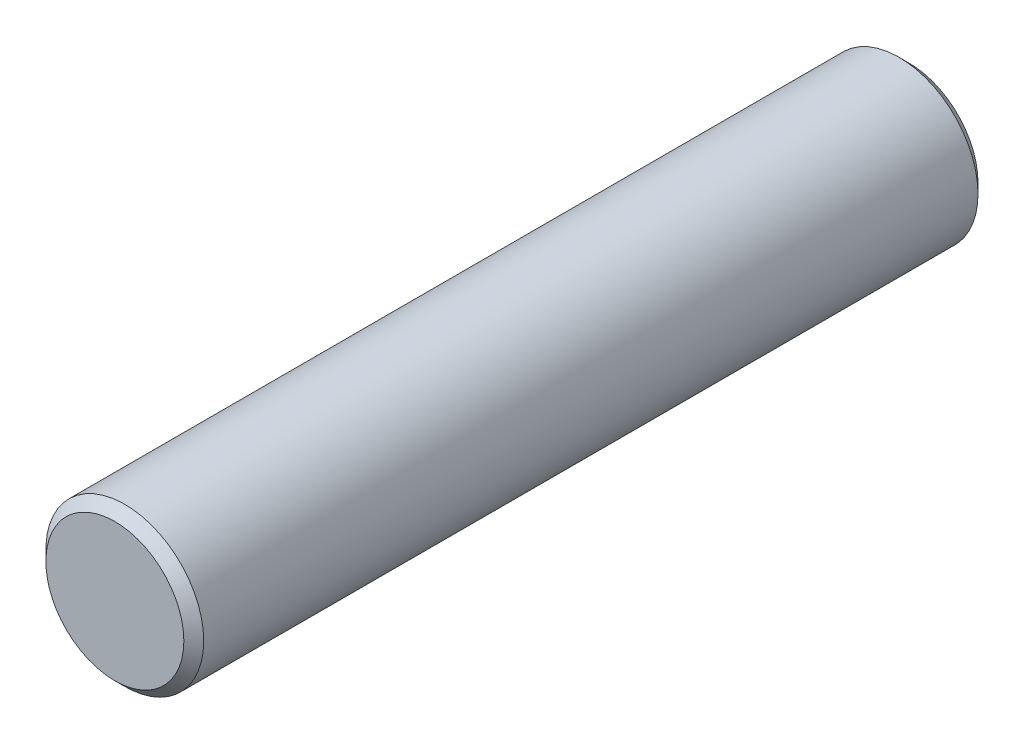
SolidWorks part; units mm, degrees
ref_plane "정면" through (0, 0, 0) normal (0, 0, 1) x (1, 0, 0)
ref_plane "윗면" through (0, 0, 0) normal (0, 1, 0) x (1, 0, 0)
ref_plane "우측면" through (0, 0, 0) normal (1, 0, 0) x (0, 0, -1)
sketch "스케치1" plane through (0, 0, 0) normal (0, 0, 1) x (1, 0, 0)
  circle A0 centre (0, 0) radius 3.975
  dimension "D1" = 7.95
extrude "보스-돌출1" add sketch "스케치1" along normal blind 40
chamfer "모따기1" distance 0.5 angle 45 2 edges at (3.975, 0, 0) (3.975, 0, 40)
